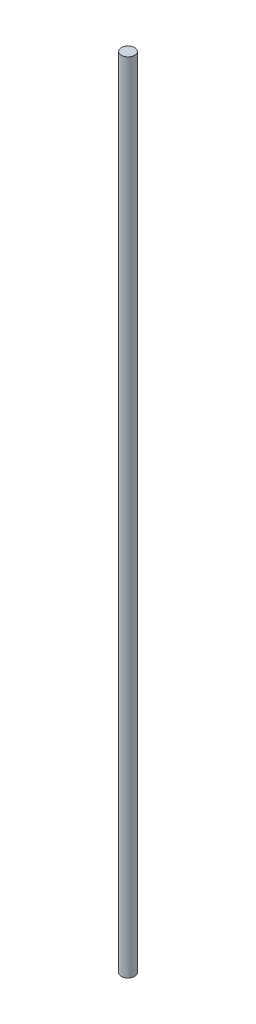
SolidWorks part; units mm, degrees
ref_plane "Front Plane" through (0, 0, 0) normal (0, 0, 1) x (1, 0, 0)
ref_plane "Top Plane" through (0, 0, 0) normal (0, 1, 0) x (1, 0, 0)
ref_plane "Right Plane" through (0, 0, 0) normal (1, 0, 0) x (0, 0, -1)
sketch "Sketch1" plane through (0, 0, 0) normal (0, 1, 0) x (1, 0, 0)
  circle A0 centre (1.3284, 0) radius 5
extrude "Boss-Extrude1" add sketch "Sketch1" along normal blind 600 contours A0
